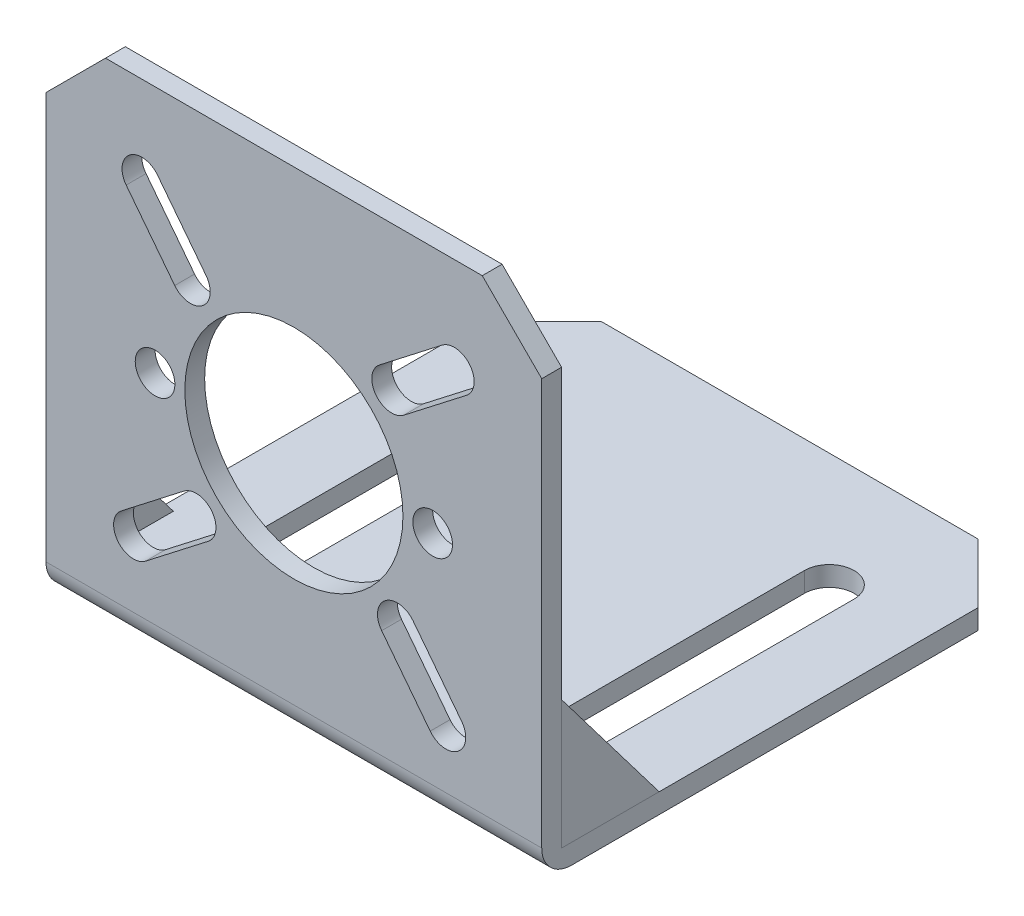
SolidWorks part; units mm, degrees
ref_plane "Front Plane" through (0, 0, 0) normal (0, 0, 1) x (1, 0, 0)
ref_plane "Top Plane" through (0, 0, 0) normal (0, 1, 0) x (1, 0, 0)
ref_plane "Right Plane" through (0, 0, 0) normal (1, 0, 0) x (0, 0, -1)
sketch "Sketch1" plane through (0, 0, 0) normal (0, 0, 1) x (1, 0, 0)
  line L0 (55, 0) -> (-55, 0) construction
  line L1 (-25, 25) -> (25, 25)
  line L2 (-25, 25) -> (-25, -25)
  line L3 (-25, -25) -> (25, -25)
  line L4 (25, 25) -> (25, -25)
  line L5 (-25, 25) -> (25, -25) construction
  line L6 (-25, -25) -> (25, 25) construction
  line L7 (0, -55) -> (0, 55) construction
  point P0 (0, 0)
  dimension "D1" = 50
  dimension "D2" = 50
extrude "Boss-Extrude1" add sketch "Sketch1" along normal blind 2
sketch "Sketch2" plane through (0, 0, 2) normal (0, 0, 1) x (1, 0, 0)
  line L0 (0, -1.1) -> (0, 1.1) construction
  line L1 (1.1, 0) -> (-1.1, 0) construction
  circle A0 centre (0, 0) radius 11
  dimension "D1" = 22
extrude "Cut-Extrude1" cut sketch "Sketch2" against normal through all
chamfer "Chamfer1" distance 6 angle 45 1 edges at (-25, 25, 1)
chamfer "Chamfer2" distance 6 angle 45 1 edges at (25, 25, 1)
sketch "Sketch3" plane through (0, 0, 2) normal (0, 0, 1) x (1, 0, 0)
  line L0 (9.8568, 10.4352) -> (16.1826, 15.3326) construction
  line L1 (8.6325, 12.0166) -> (14.9583, 16.914)
  line L2 (11.0812, 8.8537) -> (17.407, 13.7511)
  arc A0 (8.6325, 12.0166) -> (11.0812, 8.8537) centre (9.8568, 10.4352) ccw
  arc A1 (17.407, 13.7511) -> (14.9583, 16.914) centre (16.1826, 15.3326) ccw
  point P2 (13.0197, 12.8839)
  dimension "D1" = 4
  dimension "D2" = 8
extrude "Cut-Extrude2" cut sketch "Sketch3" against normal through all
pattern_circular "CirPattern1" count 4 over 360 about axis through (0, 0, 0) along (0, 0, 1) of "Cut-Extrude2"
sketch "Sketch4" plane through (0, 0, 2) normal (0, 0, 1) x (1, 0, 0)
  line L0 (1.1, 0) -> (-1.1, 0) construction
  circle A0 centre (14, 0) radius 2
  circle A1 centre (0, 0) radius 11 construction
  dimension "D1" = 4
  dimension "D2" = 14
extrude "Cut-Extrude3" cut sketch "Sketch4" against normal through all
mirror "Mirror5" about plane through (0, 0, 0) normal (1, 0, 0) of "Cut-Extrude3"
sketch "Sketch5" plane through (0, 0, 0) normal (0, 0, -1) x (-1, 0, 0)
  line L0 (0, 1.1) -> (0, -1.1) construction
  line L1 (-25, -25) -> (25, -25)
  line L2 (-25, -25) -> (-25, -23)
  line L3 (-25, -23) -> (25, -23)
  line L4 (25, -25) -> (25, -23)
  line L5 (-25, -25) -> (25, -23) construction
  line L6 (-25, -23) -> (25, -25) construction
  line L7 (25, 19) -> (25, -25) construction
  line L8 (25, -25) -> (-25, -25) construction
  point P0 (0, -24)
  dimension "D1" = 0
  dimension "D2" = 2
extrude "Boss-Extrude5" add sketch "Sketch5" along normal blind 48
chamfer "Chamfer3" distance 6 angle 45 1 edges at (25, -24, -48)
chamfer "Chamfer4" distance 6 angle 45 1 edges at (-25, -24, -48)
sketch "Sketch7" plane through (0, -25, 0) normal (0, -1, 0) x (1, 0, 0)
  line L0 (-15.5, -7.5) -> (-15.5, -36.5) construction
  line L1 (-13, -7.5) -> (-13, -36.5)
  line L2 (-18, -7.5) -> (-18, -36.5)
  line L3 (-25, 2) -> (-25, -42) construction
  line L4 (19, -48) -> (-19, -48) construction
  arc A0 (-13, -7.5) -> (-18, -7.5) centre (-15.5, -7.5) ccw
  arc A1 (-18, -36.5) -> (-13, -36.5) centre (-15.5, -36.5) ccw
  point P2 (-15.5, -22)
  dimension "D1" = 29
  dimension "D2" = 9.5
  dimension "0.5" = 5
  dimension "D3" = 9.5
  dimension "D4" = 11.5
extrude "Cut-Extrude5" cut sketch "Sketch7" against normal through all contours L1 A1 L2 A0
mirror "Mirror8" about plane through (0, 0, 0) normal (1, 0, 0) of "Cut-Extrude5"
sketch "Sketch8" plane through (25, 0, 0) normal (1, 0, 0) x (0, 0, -1)
  line L0 (0, -10.0383) -> (9.8439, -23)
  line L1 (0, 27.5) -> (0, -27.5) construction
  line L2 (42, -23) -> (0, -23) construction
  line L3 (9.8439, -23) -> (0, -23)
  line L4 (0, -23) -> (0, -10.0383)
extrude "Boss-Extrude6" add sketch "Sketch8" against normal blind 1 and the other way through all contours L0 L3 L4
mirror "Mirror9" about plane through (0, 0, 0) normal (1, 0, 0) of "Boss-Extrude6"
fillet "Fillet1" radius 3 1 edges at (0, -25, 2)
